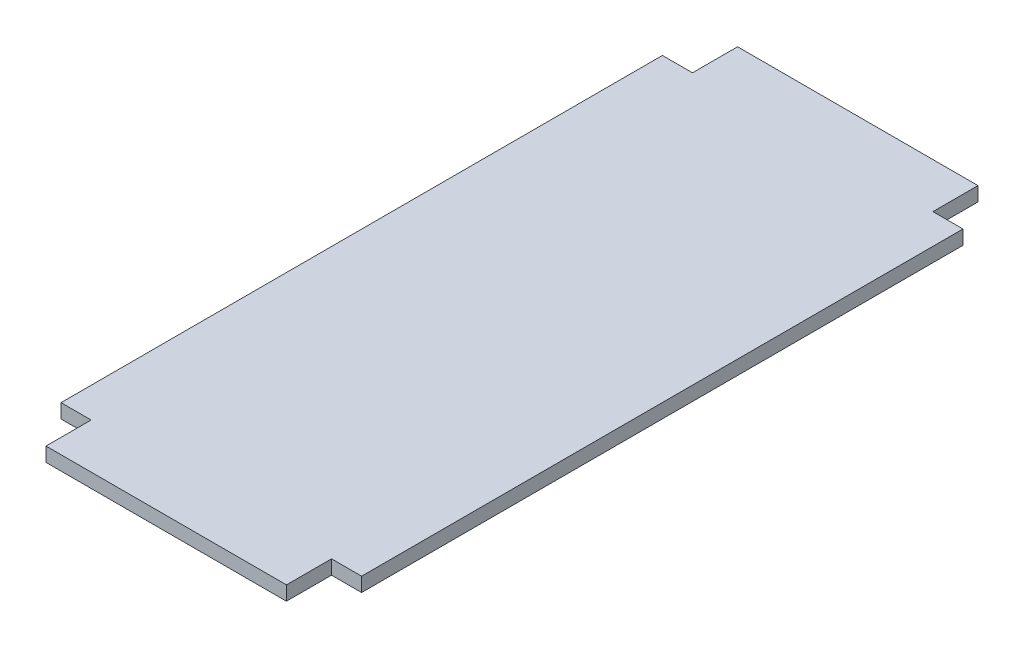
SolidWorks part; units mm, degrees
ref_plane "Front Plane" through (0, 0, 0) normal (0, 0, 1) x (1, 0, 0)
ref_plane "Top Plane" through (0, 0, 0) normal (0, 1, 0) x (1, 0, 0)
ref_plane "Right Plane" through (0, 0, 0) normal (1, 0, 0) x (0, 0, -1)
sketch "Sketch1" plane through (0, 0, 0) normal (0, 1, 0) x (1, 0, 0)
  line L0 (-31.7373, 66.4972) -> (31.7373, 66.4972) construction
  line L1 (31.7373, -73.025) -> (-31.7373, -73.025)
  line L2 (31.7373, -73.025) -> (31.7373, 73.025)
  line L3 (31.7373, 73.025) -> (-31.7373, 73.025)
  line L4 (-31.7373, -73.025) -> (-31.7373, 73.025)
  line L5 (31.7373, -73.025) -> (-31.7373, 73.025) construction
  line L6 (31.7373, 73.025) -> (-31.7373, -73.025) construction
  line L7 (-31.7373, -66.4972) -> (31.7373, -66.4972) construction
  line L8 (-31.7373, 66.4972) -> (-31.7373, -66.4972) construction
  line L9 (31.7373, 66.4972) -> (31.7373, -66.4972) construction
  line L20 (-31.7373, -73.025) -> (-25.3873, -73.025)
  line L29 (-31.7373, -73.025) -> (-31.7373, -63.5)
  line L30 (-31.7373, -63.5) -> (-25.3873, -63.5)
  line L31 (-25.3873, -73.025) -> (-25.3873, -63.5)
  line L32 (31.7373, -73.025) -> (25.3873, -73.025)
  line L33 (31.7373, -73.025) -> (31.7373, -63.5)
  line L34 (31.7373, -63.5) -> (25.3873, -63.5)
  line L35 (25.3873, -73.025) -> (25.3873, -63.5)
  line L36 (-31.7373, 73.025) -> (-25.3873, 73.025)
  line L37 (-31.7373, 73.025) -> (-31.7373, 63.5)
  line L38 (-31.7373, 63.5) -> (-25.3873, 63.5)
  line L39 (-25.3873, 73.025) -> (-25.3873, 63.5)
  line L40 (31.7373, 73.025) -> (25.3873, 73.025)
  line L41 (31.7373, 73.025) -> (31.7373, 63.5)
  line L42 (31.7373, 63.5) -> (25.3873, 63.5)
  line L43 (25.3873, 73.025) -> (25.3873, 63.5)
  point P0 (0, 0)
  point P10 (31.7373, 0)
  point P11 (31.7373, 0)
  point P24 (16.8593, -56.9625)
  point P25 (12.2936, -58.4844)
  point P26 (-20.1013, 57.3981)
  dimension "D1" = 63.4746
  dimension "D2" = 146.05
  dimension "D3" = 132.9944
  dimension "D4" = 127
  dimension "D5" = 6.35
extrude "Boss-Extrude1" add sketch "Sketch1" along normal blind 2.9972
